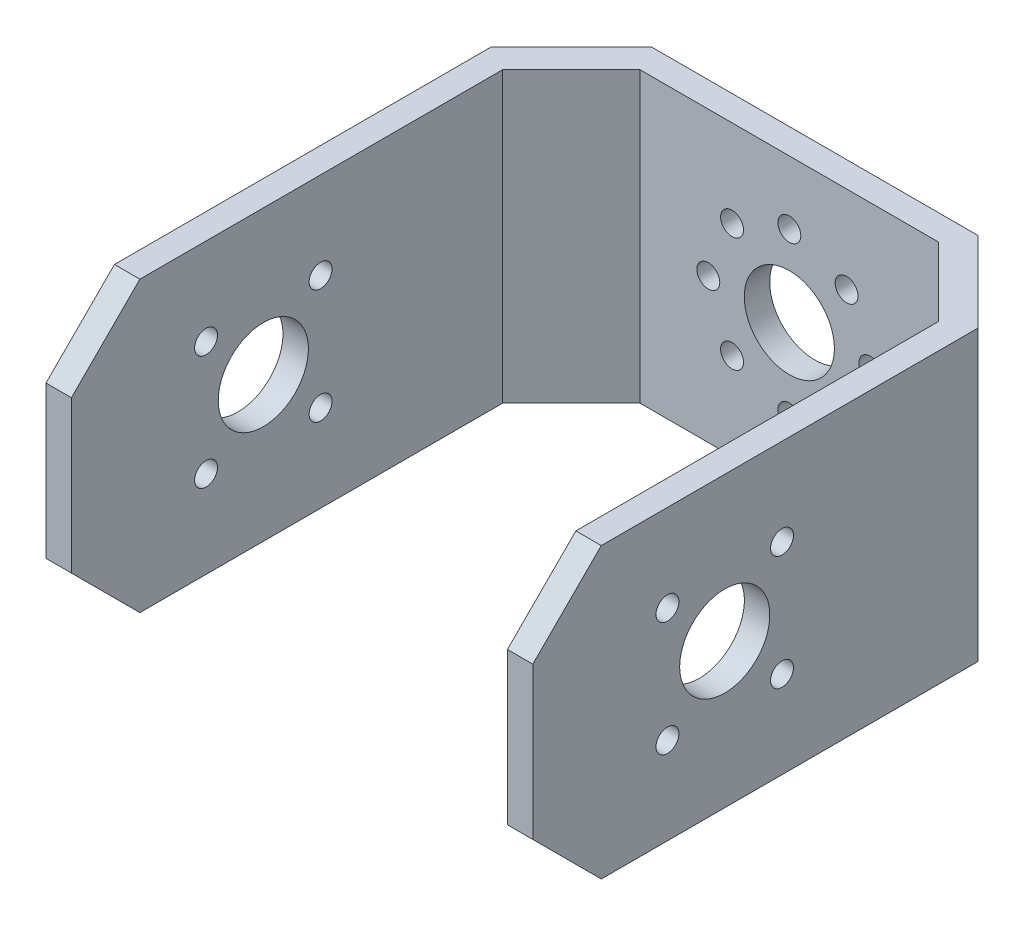
SolidWorks part; units mm, degrees
ref_plane "Front Plane" through (0, 0, 0) normal (0, 0, 1) x (1, 0, 0)
ref_plane "Top Plane" through (0, 0, 0) normal (0, 1, 0) x (1, 0, 0)
ref_plane "Right Plane" through (0, 0, 0) normal (1, 0, 0) x (0, 0, -1)
sketch "Sketch1" plane through (0, 0, 0) normal (0, 1, 0) x (1, 0, 0)
  line L0 (0, 0) -> (-21.25, 0)
  line L1 (-21.25, 0) -> (-21.25, -45.86)
  line L2 (-21.25, -45.86) -> (-19.03, -45.86)
  line L3 (-19.03, -45.86) -> (-19.03, -2.22)
  line L4 (-19.03, -2.22) -> (0, -2.22)
  line L5 (0, -2.22) -> (0, 0)
  dimension "D1" = 2.22
  dimension "D2" = 2.22
  dimension "D3" = 21.25
  dimension "D4" = 45.86
extrude "Boss-Extrude1" add sketch "Sketch1" along normal mid plane 25.21
sketch "Sketch2" plane through (-21.25, 0, 0) normal (-1, 0, 0) x (0, 0, 1)
  line L0 (39.885, 12.605) -> (45.86, 6.63)
  line L1 (0, 12.605) -> (45.86, 12.605) construction
  line L2 (45.86, 12.605) -> (45.86, -12.605) construction
  line L3 (45.86, 6.63) -> (45.86, -6.63) construction
  line L4 (45.86, -6.63) -> (39.885, -12.605)
  line L5 (0, -12.605) -> (45.86, -12.605) construction
  line L6 (39.885, -12.605) -> (39.885, 12.605) construction
  line L7 (0, 0) -> (45.86, 0) construction
  line L8 (39.885, 12.605) -> (45.86, 12.605)
  line L9 (45.86, 12.605) -> (45.86, 6.63)
  line L10 (39.885, -12.605) -> (45.86, -12.605)
  line L11 (45.86, -12.605) -> (45.86, -6.63)
  point P11 (45.86, 0)
  dimension "D1" = 13.26
  dimension "D2" = 45
extrude "Cut-Extrude1" cut sketch "Sketch2" against normal blind 32.2
sketch "Sketch3" plane through (-21.25, 0, 0) normal (-1, 0, 0) x (0, 0, 1)
  line L0 (29.11, 12.25) -> (29.11, 0) construction
  line L1 (34.11, -5) -> (24.11, -5) construction
  line L2 (34.11, -5) -> (34.11, 5) construction
  line L3 (34.11, 5) -> (24.11, 5) construction
  line L4 (24.11, -5) -> (24.11, 5) construction
  line L5 (34.11, -5) -> (24.11, 5) construction
  line L6 (34.11, 5) -> (24.11, -5) construction
  line L7 (29.11, 0) -> (45.86, 0) construction
  line L8 (45.86, 6.63) -> (45.86, -6.63) construction
  circle A0 centre (29.11, 0) radius 3.935
  circle A1 centre (24.11, 5) radius 1
  circle A2 centre (34.11, 5) radius 1
  circle A3 centre (34.11, -5) radius 1
  circle A4 centre (24.11, -5) radius 1
  dimension "D1" = 7.87
  dimension "D3" = 2
  dimension "D2" = 45
  dimension "D4" = 10
  dimension "D5" = 16.75
extrude "Cut-Extrude2" cut sketch "Sketch3" against normal blind 32.2
mirror "Mirror1" about plane through (0, 12.605, 2.22) normal (-1, 0, 0) of "Cut-Extrude1", "Boss-Extrude1", "Cut-Extrude2"
sketch "Sketch4" plane through (0, 0, 2.22) normal (0, 0, 1) x (1, 0, 0)
  line L0 (0, 9.4948) -> (0, 0) construction
  line L1 (5, -5) -> (-5, -5) construction
  line L2 (5, -5) -> (5, 5) construction
  line L3 (5, 5) -> (-5, 5) construction
  line L4 (-5, -5) -> (-5, 5) construction
  line L5 (5, -5) -> (-5, 5) construction
  line L6 (5, 5) -> (-5, -5) construction
  line L7 (7.0711, 0) -> (0, 7.0711) construction
  line L8 (7.0711, 0) -> (0, -7.0711) construction
  line L9 (0, 7.0711) -> (-7.0711, 0) construction
  line L10 (0, -7.0711) -> (-7.0711, 0) construction
  line L11 (7.0711, 0) -> (-7.0711, 0) construction
  line L12 (0, 7.0711) -> (0, -7.0711) construction
  circle A0 centre (0, 0) radius 3.935
  circle A1 centre (-5, 5) radius 1
  circle A2 centre (5, 5) radius 1
  circle A3 centre (5, -5) radius 1
  circle A4 centre (-5, -5) radius 1
  circle A5 centre (-7.0711, 0) radius 1
  circle A6 centre (0, 7.0711) radius 1
  circle A7 centre (7.0711, 0) radius 1
  circle A8 centre (0, -7.0711) radius 1
  dimension "D1" = 7.87
  dimension "D3" = 2
  dimension "D6" = 10
  dimension "D2" = 45
  dimension "D4" = 10
  dimension "D5" = 45
extrude "Cut-Extrude3" cut sketch "Sketch4" against normal blind 32.2
chamfer "Chamfer1" distance 6 angle 45 2 edges at (19.03, 0, 2.22) (-19.03, 0, 2.22)
chamfer "Chamfer2" distance 7 angle 45 2 edges at (21.25, 0, 0) (-21.25, 0, 0)
